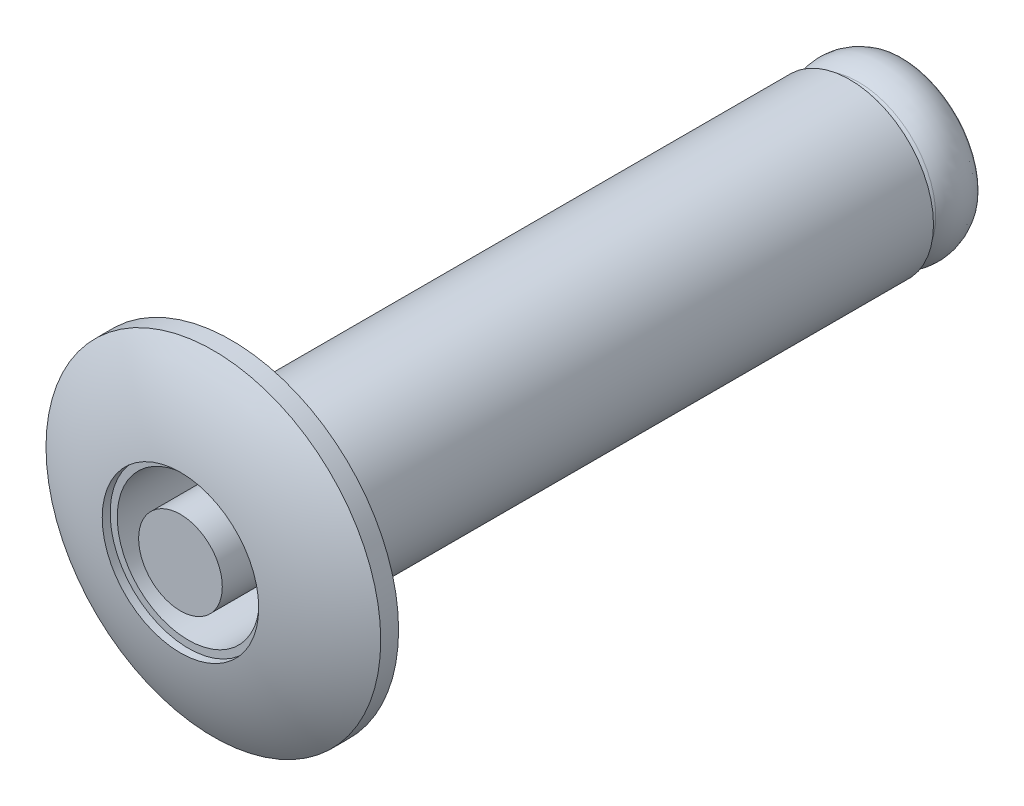
SolidWorks part; units mm, degrees
material "5052-H32"
ref_plane "Front" through (0, 0, 0) normal (0, 0, 1) x (1, 0, 0)
ref_plane "Top" through (0, 0, 0) normal (0, 1, 0) x (1, 0, 0)
ref_plane "Right" through (0, 0, 0) normal (1, 0, 0) x (0, 0, -1)
sketch "Sketch1" plane through (0, 0, 0) normal (1, 0, 0) x (0, 0, -1)
  line L0 (-24.4856, 0) -> (-1.016, 0) construction
  line L1 (-1.016, 0) -> (0, 0) construction
  line L2 (0, 0) -> (11.7348, 0) construction
  line L3 (11.7348, 0) -> (12.7508, 0) construction
  line L8 (0, 3.175) -> (0, -3.175) construction
  line L9 (11.7348, 1.5875) -> (11.7348, -1.5875) construction
  dimension "Length" = 11.7348
  dimension "Head Height" = 1.016
  dimension "D5" = 1.016
  dimension "D9" = 23.4696
  dimension "Diameter" = 3.175
  dimension "Head Diameter" = 6.35
sketch "Sketch2" plane through (0, 0, 0) normal (1, 0, 0) x (0, 0, -1)
  line L0 (-24.4856, 0) -> (-24.4856, 0.7937)
  line L1 (-24.4856, 0.7937) -> (0, 0.7937) construction
  line L2 (0, 3.175) -> (0, -3.175) construction
  line L3 (0, 0) -> (0, 3.175) construction
  line L4 (-1.016, 0) -> (-1.016, -1.8472) construction
  line L5 (11.7348, 1.5875) -> (0, 1.5875) construction
  line L6 (11.7348, 1.5875) -> (11.7348, 0) construction
  line L7 (11.8364, 0.7937) -> (11.8364, 1.4287) construction
  line L8 (11.7348, 0.7937) -> (11.7348, 1.5875) construction
  line L9 (11.8364, 1.5875) -> (12.7508, 1.5875) construction
  line L10 (12.7508, 1.5875) -> (12.7508, 0) construction
  line L11 (-1.016, 0.7938) -> (11.8364, 0.7937)
  line L12 (-24.4856, 0) -> (12.7508, 0)
  line L13 (-1.016, 0.7938) -> (-1.016, 0) construction
  line L14 (12.7508, 1.4287) -> (12.7508, 0)
  line L15 (11.8364, 0.7937) -> (11.8364, 1.4287)
  line L19 (0, 1.5875) -> (0, 3.175) construction
  line L20 (-1.016, 0.7938) -> (-24.4856, 0.7937)
  line L22 (0, 3.175) -> (-0.3387, 3.175) construction
  arc A0 (12.7508, 1.4287) -> (11.8364, 1.4287) centre (12.2936, 0.8498) ccw
  arc A2 (-0.3387, 3.175) -> (-1.016, 0.7938) centre (3.5085, 0.7938) ccw construction
  point P17 (12.7508, 0.7937)
  dimension "D3" = 0.3387
  dimension "D1" = 0.1016
  dimension "D2" = 1.4287
revolve "Revolve1" add sketch "Sketch2" angle 360 about L12
fillet "Fillet3" radius 0.127 2 edges at (1.4287, 0, -11.8364) (1.4287, 0, -12.7508)
sketch "Sketch4" plane through (0, 0, 0) normal (1, 0, 0) x (0, 0, -1)
  line L0 (0, -1.3494) -> (0, 1.3494) construction
  line L1 (-0.3387, 3.175) -> (0, 3.175)
  line L2 (0, 3.175) -> (0, 1.5875)
  line L3 (0, 1.5875) -> (11.7348, 1.5875)
  line L4 (11.7348, 1.5875) -> (11.7348, 1.3494)
  line L9 (-0.9818, 1.3494) -> (11.7348, 1.3494)
  arc A0 (-0.3387, 3.175) -> (-1.016, 0.7938) centre (3.5085, 0.7938) ccw construction
  arc A1 (-0.3387, 3.175) -> (-0.9818, 1.3494) centre (3.5085, 0.7938) ccw
  point P13 (0, 0)
  dimension "D1" = 2.6987
revolve "Revolve2" add sketch "Sketch4" angle 360 about L2
ref_plane "Plane1" through (0, 0, 1.016) normal (0, 0, 1) x (1, 0, 0)
sketch "Sketch5" plane through (0, 0, 1.016) normal (0, 0, 1) x (1, 0, 0)
  circle A4 centre (0, 0) radius 1.4843
  dimension "D1" = 2.9686
extrude "Cut-Extrude2" cut sketch "Sketch5" against normal blind 0.2032
sketch "Sketch3" plane through (0, 0, 0) normal (0, 1, 0) x (1, 0, 0)
  line L0 (0, -24.4856) -> (0.9969, -23.1863)
  line L1 (-0.7937, -24.4856) -> (0.7937, -24.4856) construction
  line L3 (0, -24.4856) -> (0, -24.9936) construction
  line L4 (0, -24.4856) -> (-0.997, -23.1863)
  line L5 (-0.997, -23.1863) -> (-0.997, -24.9936)
  line L6 (-0.997, -24.9936) -> (0.9969, -24.9936)
  line L7 (0.9969, -24.9936) -> (0.9969, -23.1863)
  dimension "D1" = 75
  dimension "D2" = 0.2032
  dimension "D3" = 0.508
extrude "Cut-Extrude1" cut sketch "Sketch3" against normal through all both and the other way through all
fillet "Fillet2" radius 0.254 1 edges at (1.5875, 0, 0)
sketch "Sketch6" plane through (0, 0, 0) normal (1, 0, 0) x (0, 0, -1)
  line L0 (-0.963, 1.4843) -> (-0.963, -1.4843) construction
  line L1 (-0.963, 1.5875) -> (-24.4856, 1.5875)
  line L2 (-0.963, 1.5875) -> (-0.963, -1.5875)
  line L3 (-0.963, -1.5875) -> (-24.4856, -1.5875)
  line L4 (-24.4856, 1.5875) -> (-24.4856, -1.5875)
  line L5 (-24.4856, -0.7937) -> (-24.4856, 0.7938) construction
  point P8 (-0.963, 0)
  dimension "D1" = 3.175
extrude "Cut-Extrude3" cut sketch "Sketch6" against normal through all both and the other way through all
equation "\"D5@Sketch1\" = \"Head Height@Sketch1\""
equation "\"D9@Sketch1\" = \"Length@Sketch1\" * 2"
equation "\"D1@Sketch2\"=\"D5@Sketch1\"*.1"
equation "\"D2@Sketch2\"=\"Diameter@Sketch1\"/2*.9"
equation "\"D3@Sketch2\"=\"Head Height@Sketch1\"/3"
equation "\"D1@Cut-Extrude2\"=\"Head Height@Sketch1\"/5"
equation "\"D1@Sketch4\"=\"Diameter@Sketch1\"*.85"
equation "\"D1@Sketch5\"=\"D1@Sketch4\"*1.1"
